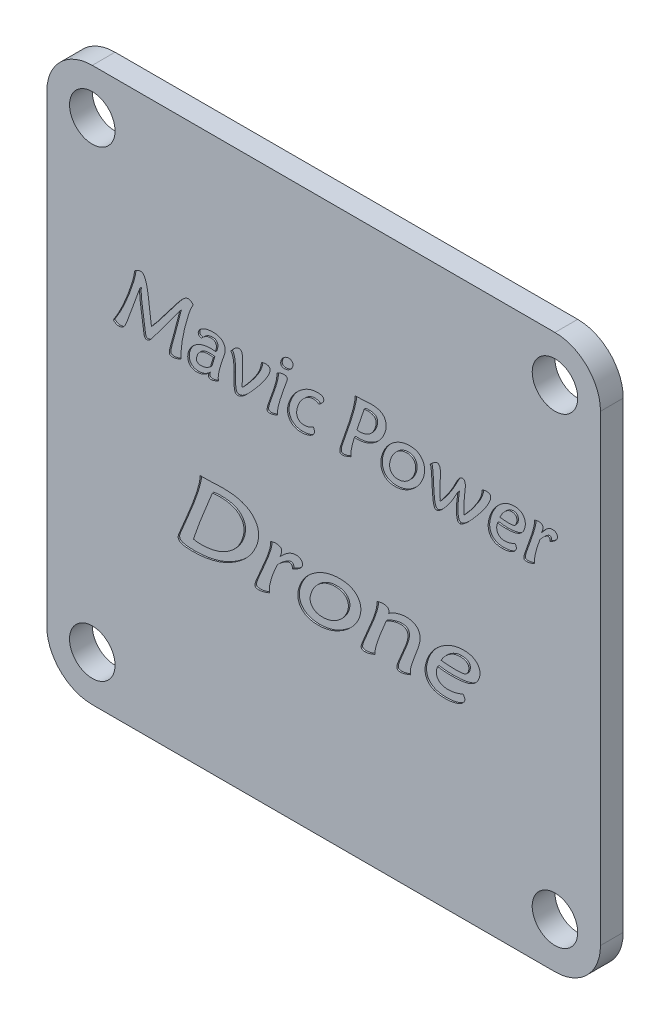
SolidWorks part; units mm, degrees
ref_plane "前视基准面" through (0, 0, 0) normal (0, 0, 1) x (1, 0, 0)
ref_plane "上视基准面" through (0, 0, 0) normal (0, 1, 0) x (1, 0, 0)
ref_plane "右视基准面" through (0, 0, 0) normal (1, 0, 0) x (0, 0, -1)
sketch "草图1" plane through (0, 0, 0) normal (0, 0, 1) x (1, 0, 0)
  line L0 (0, 18.25) -> (0, -18.25) construction
  line L1 (-15.25, 18.25) -> (15.25, 18.25)
  line L2 (-18.25, 15.25) -> (-18.25, -15.25)
  line L3 (-15.25, -18.25) -> (15.25, -18.25)
  line L4 (18.25, 15.25) -> (18.25, -15.25)
  line L5 (-18.25, 18.25) -> (18.25, -18.25) construction
  line L6 (-18.25, -18.25) -> (18.25, 18.25) construction
  line L7 (-18.25, 0) -> (18.25, 0) construction
  circle A0 centre (-15.25, 15.25) radius 1.5
  circle A1 centre (15.25, 15.25) radius 1.5
  circle A2 centre (15.25, -15.25) radius 1.5
  circle A3 centre (-15.25, -15.25) radius 1.5
  arc A4 (-15.25, -18.25) -> (-18.25, -15.25) centre (-15.25, -15.25) cw
  arc A5 (15.25, -18.25) -> (18.25, -15.25) centre (15.25, -15.25) ccw
  arc A6 (18.25, 15.25) -> (15.25, 18.25) centre (15.25, 15.25) ccw
  arc A7 (-18.25, 15.25) -> (-15.25, 18.25) centre (-15.25, 15.25) cw
  point P0 (0, 0)
  dimension "D1" = 3
  dimension "D2" = 30.5
  dimension "D5" = 3
  dimension "D3" = 36.5
  dimension "D4" = 36.5
extrude "凸台-拉伸1" add sketch "草图1" along normal blind 1.5
sketch "草图3" plane through (0, 0, 1.5) normal (0, 0, 1) x (1, 0, 0)
  text T0 "<b><i>Mavic Power</i></b>" font "华文新魏" height in points 15
extrude "切除-拉伸2" cut sketch "草图3" against normal blind 0.1
sketch "草图4" plane through (0, 0, 1.5) normal (0, 0, 1) x (1, 0, 0)
  text T0 "<b><i>Drone</i></b>" font "华文新魏" height in points 18
extrude "切除-拉伸3" cut sketch "草图4" against normal blind 0.1
